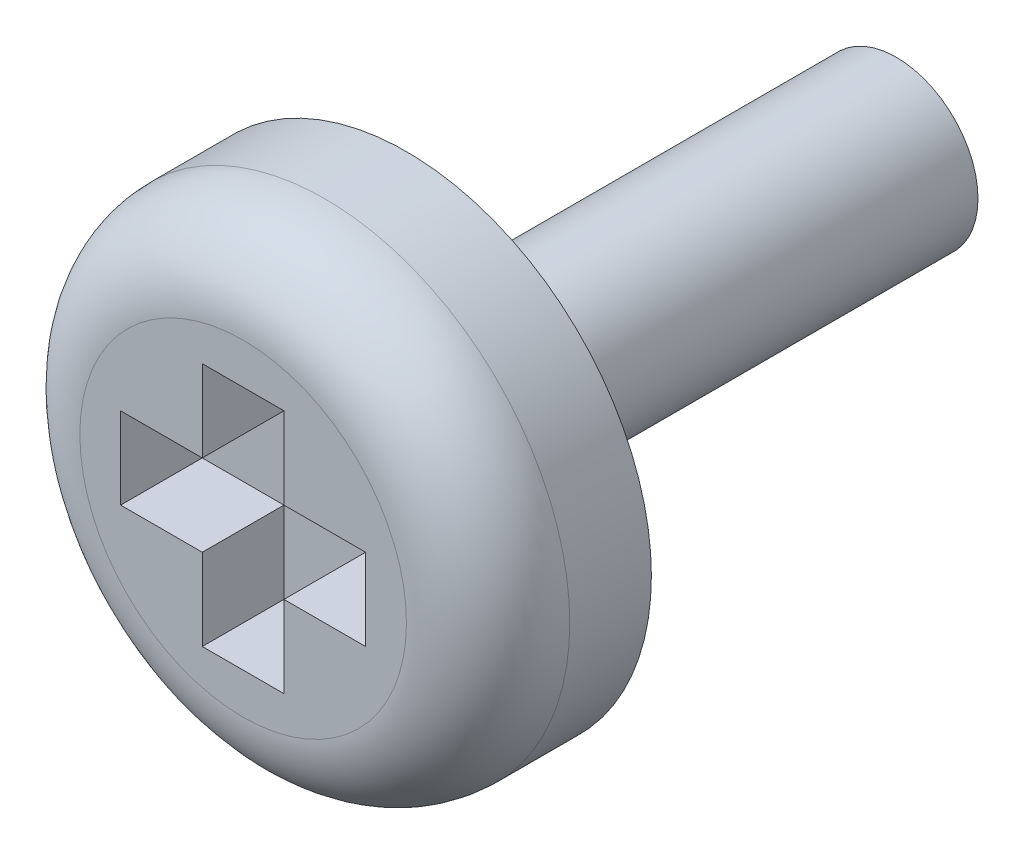
SolidWorks part; units mm, degrees
ref_plane "前视基准面" through (0, 0, 0) normal (0, 0, 1) x (1, 0, 0)
ref_plane "上视基准面" through (0, 0, 0) normal (0, 1, 0) x (1, 0, 0)
ref_plane "右视基准面" through (0, 0, 0) normal (1, 0, 0) x (0, 0, -1)
sketch "草图1" plane through (0, 0, 0) normal (0, 0, 1) x (1, 0, 0)
  circle A0 centre (0, 0) radius 0.5
  dimension "D1" = 1
extrude "凸台-拉伸1" add sketch "草图1" along normal blind 3
sketch "草图2" plane through (0, 0, 3) normal (0, 0, 1) x (1, 0, 0)
  circle A0 centre (0, 0) radius 1.5
  dimension "D1" = 3
extrude "凸台-拉伸2" add sketch "草图2" along normal blind 1
fillet "圆角1" radius 0.5 1 edges at (1.5, 0, 4)
sketch "草图3" plane through (0, 0, 4) normal (0, 0, 1) x (1, 0, 0)
  line L0 (-0.25, 0.75) -> (0.25, -0.75) construction
  line L1 (-0.75, 0.25) -> (-0.25, 0.25)
  line L2 (-0.75, 0.25) -> (-0.75, -0.25)
  line L3 (-0.75, -0.25) -> (-0.25, -0.25)
  line L4 (0.75, 0.25) -> (0.75, -0.25)
  line L5 (-0.25, 0.75) -> (0.25, 0.75)
  line L6 (-0.25, 0.75) -> (-0.25, 0.25)
  line L7 (-0.25, -0.75) -> (0.25, -0.75)
  line L8 (0.25, 0.75) -> (0.25, 0.25)
  line L9 (-0.25, -0.75) -> (0.25, 0.75) construction
  line L10 (-0.75, 0.25) -> (0.75, -0.25) construction
  line L11 (-0.75, -0.25) -> (0.75, 0.25) construction
  line L12 (0.25, 0.25) -> (0.75, 0.25)
  line L13 (0.25, -0.25) -> (0.25, -0.75)
  line L14 (-0.25, -0.25) -> (-0.25, -0.75)
  line L15 (0.25, -0.25) -> (0.75, -0.25)
  point P8 (0, 0)
  point P9 (0, 0)
  dimension "D1" = 1.5
  dimension "D2" = 1.5
  dimension "D3" = 0.5
  dimension "D4" = 0.5
extrude "切除-拉伸1" cut sketch "草图3" against normal blind 0.5
